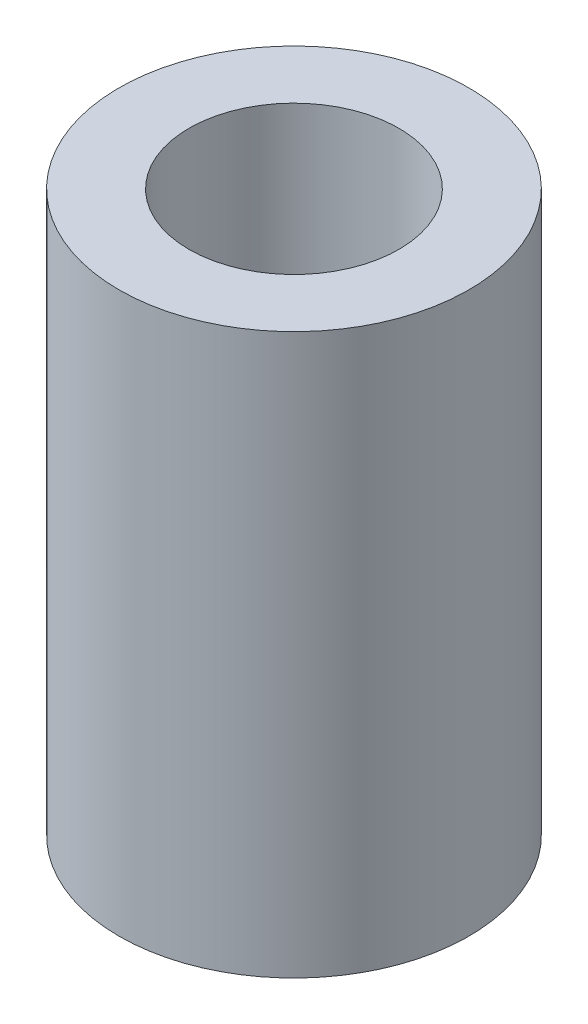
SolidWorks part; units mm, degrees
ref_plane "Plan de face" through (0, 0, 0) normal (0, 0, 1) x (1, 0, 0)
ref_plane "Plan de dessus" through (0, 0, 0) normal (0, 1, 0) x (1, 0, 0)
ref_plane "Plan de droite" through (0, 0, 0) normal (1, 0, 0) x (0, 0, -1)
sketch "Esquisse1" plane through (0, 0, 0) normal (0, 1, 0) x (1, 0, 0)
  circle A0 centre (0, 0) radius 3
  circle A1 centre (0, 0) radius 5
  dimension "D1" = 6
  dimension "D2" = 10
extrude "Boss.-Extru.1" add sketch "Esquisse1" along normal blind 16
